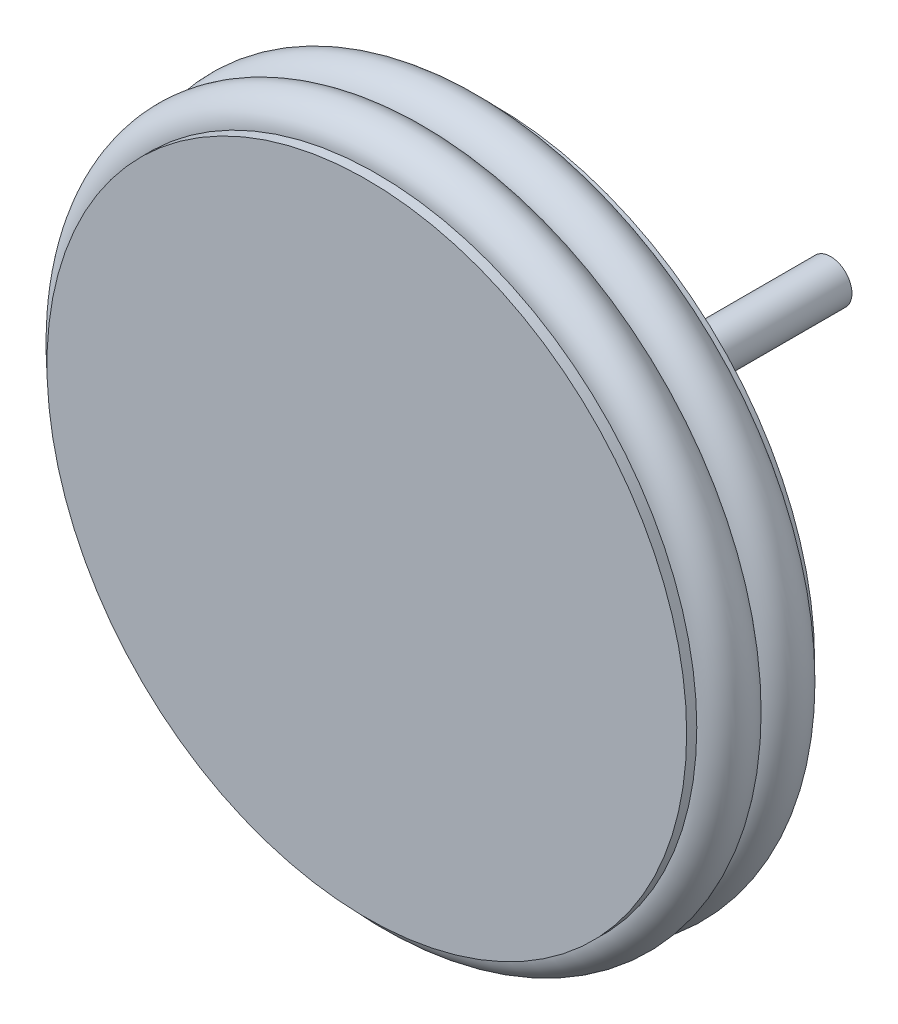
SolidWorks part; units mm, degrees
ref_plane "Front Plane" through (0, 0, 0) normal (0, 0, 1) x (1, 0, 0)
ref_plane "Top Plane" through (0, 0, 0) normal (0, 1, 0) x (1, 0, 0)
ref_plane "Right Plane" through (0, 0, 0) normal (1, 0, 0) x (0, 0, -1)
sketch "Sketch1" plane through (0, 0, 0) normal (0, 0, 1) x (1, 0, 0)
  circle A0 centre (0, 0) radius 60
  dimension "D1" = 120
sweep "Sweep1" add path "Sketch1" circular profile diameter 10 parameters "D3"=10
ref_plane "Plane1" through (0, 0, 15) normal (0, 0, 1) x (1, 0, 0)
sketch "Sketch12" plane through (0, 0, 15) normal (0, 0, 1) x (1, 0, 0)
  circle A0 centre (0, 0) radius 60
  dimension "D1" = 120
extrude "Boss-Extrude1" add sketch "Sketch12" along normal blind 2 separate body
pattern_linear "LPattern1" count 2 spacing 22 along (0, 0, -1) of "Boss-Extrude1"
sketch "Sketch13" plane through (0, 0, -7) normal (0, 0, -1) x (-1, 0, 0)
  circle A0 centre (0, 0) radius 20
  dimension "D1" = 40
extrude "Boss-Extrude2" add sketch "Sketch13" along normal blind 3
sketch "Sketch14" plane through (0, 0, -10) normal (0, 0, -1) x (-1, 0, 0)
  circle A0 centre (0, 0) radius 4
  dimension "D1" = 8
extrude "Boss-Extrude3" add sketch "Sketch14" along normal blind 60
sketch "Sketch15" plane through (0, 0, -70) normal (0, 0, -1) x (-1, 0, 0)
  circle A0 centre (0, 0) radius 3
  dimension "D1" = 6
extrude "Boss-Extrude4" [suppressed] add sketch "Sketch15" along normal blind 80
pattern_linear "LPattern5" count 2 spacing 10.1 along (0, 0, 1) of "Sweep1"
